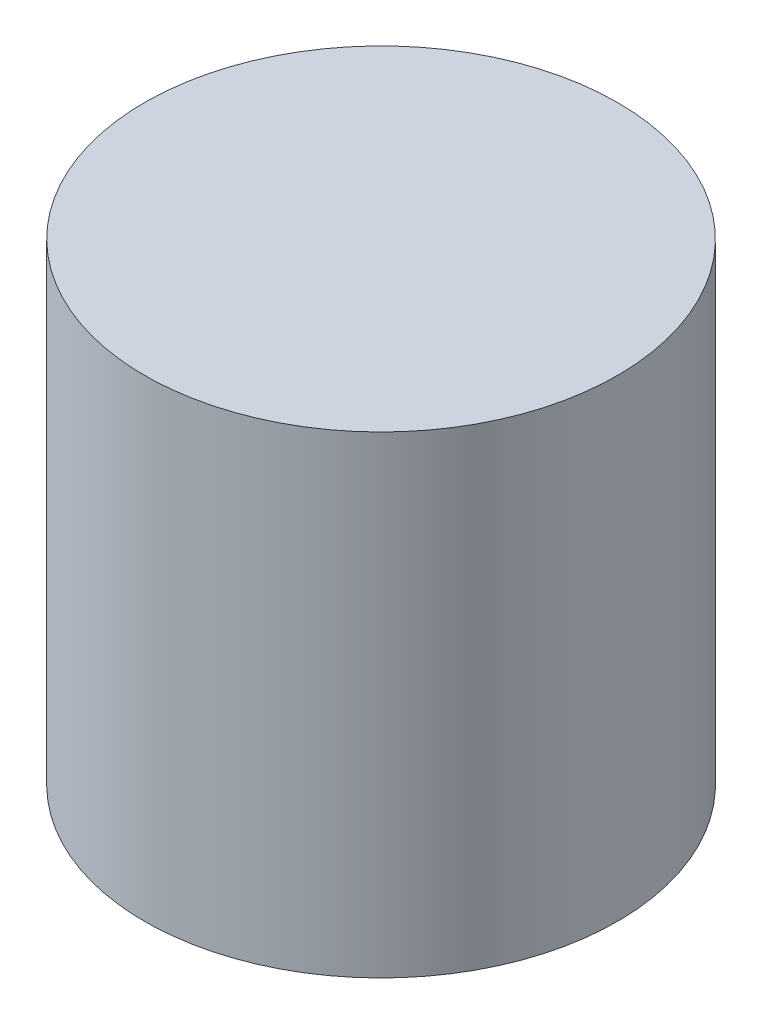
SolidWorks part; units mm, degrees
material "Acciaio al carbonio semplice"
ref_plane "Piano frontale" through (0, 0, 0) normal (0, 0, 1) x (1, 0, 0)
ref_plane "Piano superiore" through (0, 0, 0) normal (0, 1, 0) x (1, 0, 0)
ref_plane "Piano destro" through (0, 0, 0) normal (1, 0, 0) x (0, 0, -1)
sketch "Schizzo1" plane through (0, 0, 0) normal (0, 0, 1) x (1, 0, 0)
  line L0 (0, 0) -> (0, 34.1434) construction
  line L2 (-14, 30) -> (0, 30)
  line L3 (-14, 0) -> (-16, 0)
  line L4 (-16, 0) -> (-16, 32)
  line L5 (-16, 32) -> (0, 32)
  line L6 (0, 32) -> (0, 30)
  line L10 (-14, 0) -> (-14, 30)
  point P10 (-12, 0.5617)
  dimension "D1" = 28
  dimension "D2" = 30
  dimension "D3" = 32
  dimension "D4" = 32
revolve "Rivoluzione1" add sketch "Schizzo1" angle 360 about L0
